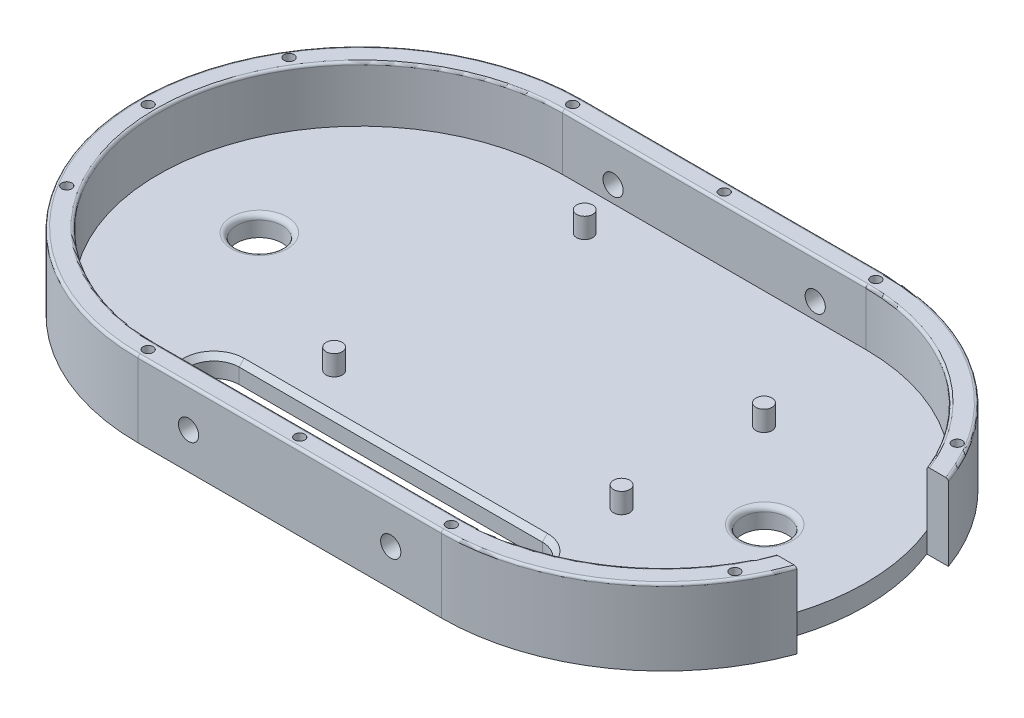
SolidWorks part; units mm, degrees
ref_plane "Front Plane" through (0, 0, 0) normal (0, 0, 1) x (1, 0, 0)
ref_plane "Top Plane" through (0, 0, 0) normal (0, 1, 0) x (1, 0, 0)
ref_plane "Right Plane" through (0, 0, 0) normal (1, 0, 0) x (0, 0, -1)
sketch "Sketch1" plane through (0, 0, 0) normal (0, 1, 0) x (1, 0, 0)
  line L1 (-30, 44) -> (30, 44)
  line L3 (30, -44) -> (-30, -44)
  arc A0 (30, -44) -> (30, 44) centre (30, 0) ccw
  arc A1 (-30, -44) -> (-30, 44) centre (-30, 0) cw
  point P10 (0, -44)
  point P11 (0, 44)
  dimension "D2" = 30
extrude "Boss-Extrude1" add sketch "Sketch1" along normal blind 15
shell "Shell1" thickness 4
sketch "Sketch2" plane through (0, 4, 0) normal (0, 1, 0) x (1, 0, 0)
  line L0 (-74, 0) -> (74, 0) construction
  line L1 (-30, 44) -> (-30, -44) construction
  line L2 (30, 44) -> (30, -44) construction
  line L3 (-74, -29) -> (74, -29) construction
  line L4 (-30, -44) -> (30, -44) construction
  line L5 (-30, -29) -> (30, -29) construction
  line L6 (-30, -24) -> (30, -24)
  line L7 (-30, -34) -> (30, -34)
  arc A0 (-30, 44) -> (-30, -44) centre (-30, 0) ccw construction
  arc A1 (30, -44) -> (30, 44) centre (30, 0) ccw construction
  arc A2 (-30, -24) -> (-30, -34) centre (-30, -29) ccw
  arc A3 (30, -34) -> (30, -24) centre (30, -29) ccw
  point P22 (0, -29)
  dimension "D1" = 15
extrude "Cut-Extrude1" cut sketch "Sketch2" against normal blind 15
sketch "Sketch3" plane through (0, 15, 0) normal (0, 1, 0) x (1, 0, 0)
  line L0 (0, 44) -> (0, -44) construction
  line L1 (30, 44) -> (-30, 44) construction
  line L2 (-30, -44) -> (30, -44) construction
  line L3 (-74, 0) -> (74, 0) construction
  line L4 (-74, 0) -> (-72, 0) construction
  line L5 (-72, -42) -> (-72, 42) construction
  line L6 (-72, 42) -> (72, 42) construction
  line L7 (-72, -42) -> (72, -42) construction
  line L8 (72, -42) -> (72, 42) construction
  line L9 (-30, 44) -> (-30, -51.0688) construction
  line L10 (-87.5621, 22) -> (-68.1051, 22) construction
  line L11 (-66.1051, 0) -> (-66.1051, 34.9906) construction
  line L12 (-66.1051, 0) -> (-66.1051, -31.6276) construction
  line L13 (-66.1051, 22) -> (87.5621, 22) construction
  line L14 (-66.1051, -22) -> (87.5621, -22) construction
  line L15 (66.1051, 0) -> (66.1051, -31.6276) construction
  line L16 (66.1051, 0) -> (66.1051, 34.9906) construction
  arc A0 (-30, 44) -> (-30, -44) centre (-30, 0) ccw construction
  arc A1 (30, -44) -> (30, 44) centre (30, 0) ccw construction
  circle A2 centre (-30, -42) radius 1
  circle A3 centre (0, -42) radius 1
  circle A4 centre (30, -42) radius 1
  circle A5 centre (-30, 42) radius 1
  circle A6 centre (0, 42) radius 1
  circle A7 centre (30, 42) radius 1
  circle A8 centre (66.1051, 22) radius 1
  circle A9 centre (72, 0) radius 1
  circle A10 centre (-66.1051, 22) radius 1
  circle A11 centre (-72, 0) radius 1
  circle A12 centre (-66.1051, -22) radius 1
  circle A13 centre (66.1051, -22) radius 1
  point P18 (0, 42)
  point P21 (0, -42)
  dimension "D1" = 22
extrude "Cut-Extrude2" cut sketch "Sketch3" against normal blind 6
fillet "Fillet1" radius 0.5 8 edges at (0, 15, 44) (-74, 15, 0) (0, 15, -44) (0, 15, 40) (-70, 15, 0) (0, 15, -40) (74, 15, 0) (70, 15, 0)
sketch "Sketch4" plane through (0, 0, 44) normal (0, 0, 1) x (1, 0, 0)
  line L0 (-20, 7.25) -> (30, 7.25) construction
  line L1 (-30, 14.5) -> (-30, 0) construction
  line L2 (30, 14.5) -> (30, 0) construction
  line L3 (0, 15) -> (0, 0) construction
  line L4 (-30, 15) -> (30, 15) construction
  line L5 (-30, 7.25) -> (-20, 7.25) construction
  circle A0 centre (-20, 7.25) radius 2
  circle A1 centre (20, 7.25) radius 2
extrude "Cut-Extrude3" cut sketch "Sketch4" against normal through all
chamfer "Chamfer1" distance 1 angle 45 4 edges at (35, 4, 29) (0, 4, 34) (0, 4, 24) (-35, 4, 29)
sketch "Sketch5" plane through (0, 0, 0) normal (0, -1, 0) x (1, 0, 0)
  line L2 (30, 35) -> (-30, 35)
  line L3 (30, -35) -> (-30, -35)
  arc A1 (30, -35) -> (30, 35) centre (30, 0) ccw
  arc A2 (-30, 35) -> (-30, -35) centre (-30, 0) ccw
sketch "Sketch6" plane through (0, 0, 0) normal (0, 1, 0) x (1, 0, 0)
  line L0 (70, 0) -> (83, 0) construction
  line L1 (83, 0) -> (83, 15) construction
  line L2 (83, 0) -> (83, -15) construction
  line L3 (83, 15) -> (67.081, 15)
  line L4 (83, 15) -> (83, -15)
  line L5 (83, -15) -> (67.081, -15)
  arc A0 (67.081, -15) -> (67.081, 15) centre (30, 0) ccw
extrude "Cut-Extrude7" cut sketch "Sketch6" along normal through all
sketch "Sketch9" plane through (0, 4, 0) normal (0, 1, 0) x (1, 0, 0)
  line L0 (0, 0) -> (0, 8) construction
  line L1 (70, 0) -> (-70, 0) construction
  line L3 (0, 8) -> (33.03, 8) construction
  line L5 (33.03, 8) -> (33.03, 16.83) construction
  line L6 (33.03, 8) -> (33.03, -11.34) construction
  line L7 (0, 8) -> (-17.78, 8) construction
  line L8 (-17.78, 8) -> (-17.78, 32.16) construction
  line L9 (-17.78, 8) -> (-19.03, 8) construction
  line L10 (-19.03, 8) -> (-19.03, -16.16) construction
  circle A2 centre (33.03, 16.83) radius 1.6
  circle A3 centre (33.03, -11.34) radius 1.6
  circle A4 centre (-17.78, 32.16) radius 1.6
  circle A5 centre (-19.03, -16.16) radius 1.6
  arc A6 (67.081, -15) -> (67.081, 15) centre (30, 0) ccw construction
  arc A7 (-30, 40) -> (-30, -40) centre (-30, 0) ccw construction
  dimension "D5" = 24.16
  dimension "D3" = 19.34
  dimension "D4" = 17.78
  dimension "D6" = 1.25
  dimension "D8" = 8
  dimension "D1" = 33.03
  dimension "D2" = 8.83
  dimension "D7" = 24.16
extrude "Boss-Extrude3" add sketch "Sketch9" along normal blind 4
sketch "Sketch10" plane through (0, 4, 0) normal (0, 1, 0) x (1, 0, 0)
  line L0 (70, 0) -> (-70, 0) construction
  line L1 (70, 0) -> (50, 0) construction
  line L2 (-70, 0) -> (-50, 0) construction
  arc A0 (67.081, -15) -> (67.081, 15) centre (30, 0) ccw construction
  arc A1 (-30, 40) -> (-30, -40) centre (-30, 0) ccw construction
  circle A2 centre (50, 0) radius 4.5
  circle A3 centre (-50, 0) radius 4.5
extrude "Cut-Extrude8" cut sketch "Sketch10" against normal blind 10
fillet "Fillet2" radius 1 2 edges at (-50, 4, 4.5) (50, 4, 4.5)
